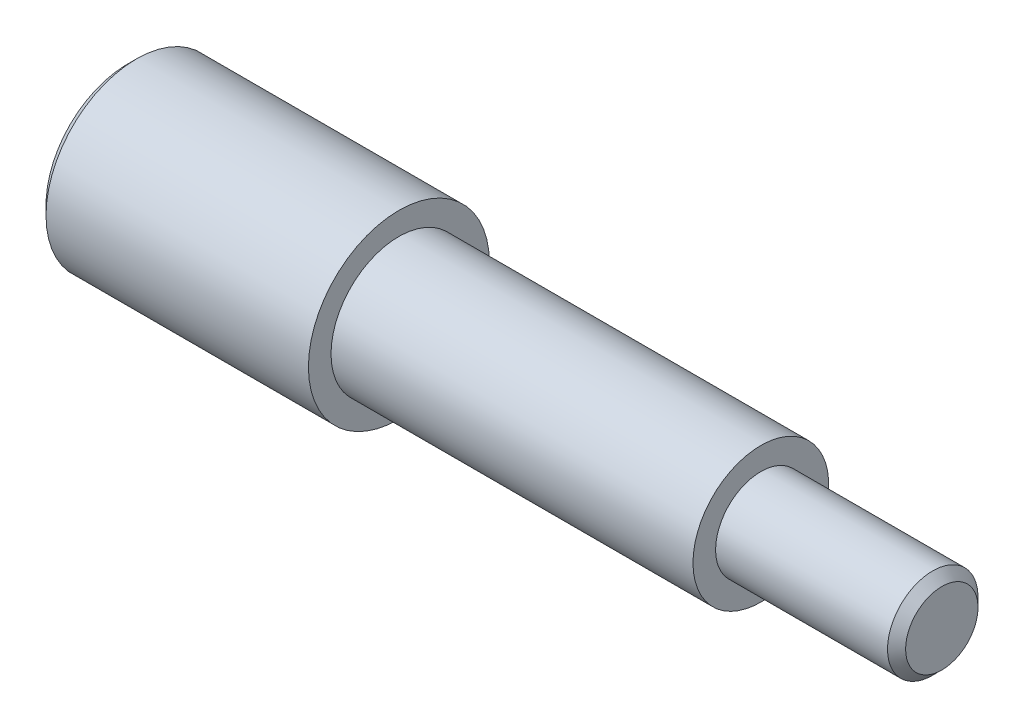
SolidWorks part; units mm, degrees
material "AISI 1020"
ref_plane "Front Plane" through (0, 0, 0) normal (0, 0, 1) x (1, 0, 0)
ref_plane "Top Plane" through (0, 0, 0) normal (0, 1, 0) x (1, 0, 0)
ref_plane "Right Plane" through (0, 0, 0) normal (1, 0, 0) x (0, 0, -1)
sketch "Sketch1" plane through (0, 0, 0) normal (0, 0, 1) x (1, 0, 0)
  line L0 (0, 0) -> (114.3, 0)
  line L10 (0, 0) -> (0, 12.7)
  line L11 (0, 12.7) -> (38.1, 12.7)
  line L12 (38.1, 12.7) -> (38.1, 9.525)
  line L13 (38.1, 9.525) -> (88.9, 9.525)
  line L14 (88.9, 9.525) -> (88.9, 6.35)
  line L15 (88.9, 6.35) -> (114.3, 6.35)
  line L23 (114.3, 6.35) -> (114.3, 0)
  point P3 (101.6, 6.35)
  dimension "D2" = 12.7
  dimension "D3" = 38.1
  dimension "D4" = 9.525
  dimension "D5" = 50.8
  dimension "D6" = 6.35
  dimension "D7" = 25.4
revolve "Shaft" add sketch "Sketch1" angle 360 about L0
chamfer "Chamfer1" distance 1.27 angle 45 2 edges at (114.3, 0, 6.35) (0, 0, 12.7)
